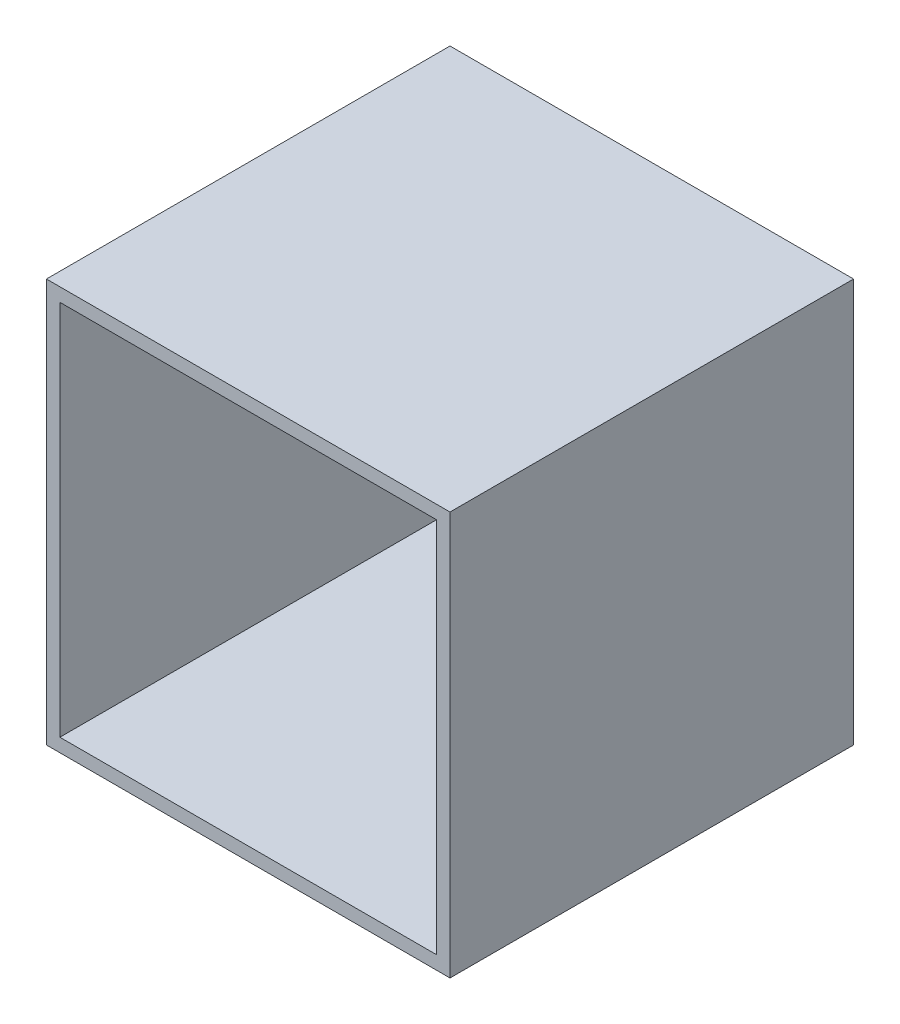
SolidWorks part; units mm, degrees
ref_plane "Front Plane" through (0, 0, 0) normal (0, 0, 1) x (1, 0, 0)
ref_plane "Top Plane" through (0, 0, 0) normal (0, 1, 0) x (1, 0, 0)
ref_plane "Right Plane" through (0, 0, 0) normal (1, 0, 0) x (0, 0, -1)
sketch "Sketch1" plane through (0, 0, 0) normal (0, 1, 0) x (1, 0, 0)
  line L1 (-38.1, -38.1) -> (38.1, -38.1)
  line L2 (-38.1, -38.1) -> (-38.1, 38.1)
  line L3 (-38.1, 38.1) -> (38.1, 38.1)
  line L4 (38.1, -38.1) -> (38.1, 38.1)
  line L5 (-38.1, -38.1) -> (38.1, 38.1) construction
  line L6 (-38.1, 38.1) -> (38.1, -38.1) construction
  point P0 (0, 0)
  dimension "D1" = 76.2
  dimension "D2" = 76.2
extrude "box" add sketch "Sketch1" along normal blind 76.2
shell "hollow it" thickness 2.54
sketch "Sketch2" plane through (0, 0, -38.1) normal (0, 0, -1) x (-1, 0, 0)
  line L0 (-38.1, 76.2) -> (38.1, 76.2) construction
  line L1 (-27.94, 69.85) -> (-21.59, 69.85)
  line L2 (-27.94, 69.85) -> (-27.94, 6.35)
  line L3 (-27.94, 6.35) -> (-21.59, 6.35)
  line L4 (-21.59, 69.85) -> (-21.59, 6.35)
  line L6 (-38.1, 76.2) -> (-38.1, 0) construction
  dimension "D1" = 6.35
  dimension "D2" = 63.5
  dimension "D3" = 6.35
  dimension "D4" = 10.16
extrude "slider track" cut sketch "Sketch2" against normal up to surface (2.54 mm away) up to face at (0, 38.1, -35.56)
sketch "Sketch4" plane through (0, 0, -38.1) normal (0, 0, -1) x (-1, 0, 0)
  line L0 (-38.1, 76.2) -> (38.1, 76.2) construction
  circle A0 centre (0, 57.15) radius 6.35
  dimension "D1" = 12.7
  dimension "D2" = 19.05
extrude "button large ring" cut sketch "Sketch4" against normal blind 1.27
sketch "Sketch5" plane through (0, 0, -36.83) normal (0, 0, -1) x (-1, 0, 0)
  circle A0 centre (0, 57.15) radius 3.175
  circle A1 centre (0, 57.15) radius 6.35 construction
  dimension "D2" = 6.35
  dimension "D1" = 0
extrude "button small hole" cut sketch "Sketch5" against normal blind 1.27
sketch "Sketch6" plane through (0, 0, -38.1) normal (0, 0, -1) x (-1, 0, 0)
  line L0 (-3.2977, 25.4) -> (-3.2977, 31.75)
  line L1 (-3.2977, 31.75) -> (3.0523, 31.75)
  line L2 (3.0523, 31.75) -> (3.0523, 25.4)
  line L3 (3.0523, 25.4) -> (9.4023, 25.4)
  line L4 (9.4023, 25.4) -> (9.4023, 19.05)
  line L5 (9.4023, 19.05) -> (3.0523, 19.05)
  line L6 (3.0523, 19.05) -> (3.0523, 12.7)
  line L7 (3.0523, 12.7) -> (-3.2977, 12.7)
  line L8 (-3.2977, 12.7) -> (-3.2977, 19.05)
  line L9 (-3.2977, 19.05) -> (-9.6477, 19.05)
  line L10 (-9.6477, 19.05) -> (-9.6477, 25.4)
  line L11 (-9.6477, 25.4) -> (-3.2977, 25.4)
  line L12 (-38.1, 0) -> (38.1, 0) construction
  dimension "D1" = 6.35
  dimension "D2" = 6.35
  dimension "D3" = 6.35
  dimension "D4" = 6.35
  dimension "D5" = 6.35
  dimension "D6" = 6.35
  dimension "D7" = 6.35
  dimension "D8" = 6.35
  dimension "D9" = 6.35
  dimension "D10" = 12.7
extrude "dpad large shape" cut sketch "Sketch6" against normal blind 1.27
sketch "Sketch7" plane through (0, 0, -36.83) normal (0, 0, -1) x (-1, 0, 0)
  line L0 (-3.2977, 25.4) -> (-9.6477, 25.4) construction
  line L1 (-9.6477, 25.4) -> (-9.6477, 19.05) construction
  line L2 (3.0523, 12.7) -> (3.0523, 19.05) construction
  line L3 (-3.2977, 12.7) -> (3.0523, 12.7) construction
  line L4 (3.0523, 19.05) -> (9.4023, 19.05) construction
  line L5 (9.4023, 19.05) -> (9.4023, 25.4) construction
  line L6 (3.0523, 25.4) -> (3.0523, 31.75) construction
  line L7 (-3.2977, 31.75) -> (-3.2977, 25.4) construction
  line L8 (3.0523, 31.75) -> (-3.2977, 31.75) construction
  circle A0 centre (-0.1227, 28.575) radius 1.397
  circle A1 centre (6.2273, 22.225) radius 1.397
  circle A2 centre (-0.1227, 15.875) radius 1.397
  circle A3 centre (-6.4727, 22.225) radius 1.397
  point P12 (3.0523, 15.875)
  point P17 (6.2273, 19.05)
  dimension "D3" = 2.794
  dimension "D6" = 2.794
  dimension "D9" = 2.794
  dimension "D13" = 2.794
  dimension "D1" = 3.175
  dimension "D2" = 3.175
  dimension "D4" = 3.175
  dimension "D5" = 3.175
  dimension "D7" = 3.175
  dimension "D8" = 3.175
  dimension "D10" = 3.175
  dimension "D11" = 3.175
  dimension "D12" = 3.175
extrude "dpad tiny holes" cut sketch "Sketch7" against normal blind 1.27
sketch "Sketch8" plane through (0, 0, -38.1) normal (0, 0, -1) x (-1, 0, 0)
  line L0 (38.1, 76.2) -> (38.1, 0) construction
  circle A0 centre (21.336, 43.0507) radius 12.7
  dimension "D1" = 25.4
  dimension "D2" = 16.764
extrude "dial large ring" cut sketch "Sketch8" against normal blind 1.27
ref_point "dial center"
sketch "Sketch9" plane through (0, 0, -36.83) normal (0, 0, -1) x (-1, 0, 0)
  circle A0 centre (21.336, 43.0507) radius 3.175
  dimension "D1" = 6.35
extrude "dial small hole" cut sketch "Sketch9" against normal blind 1.27
